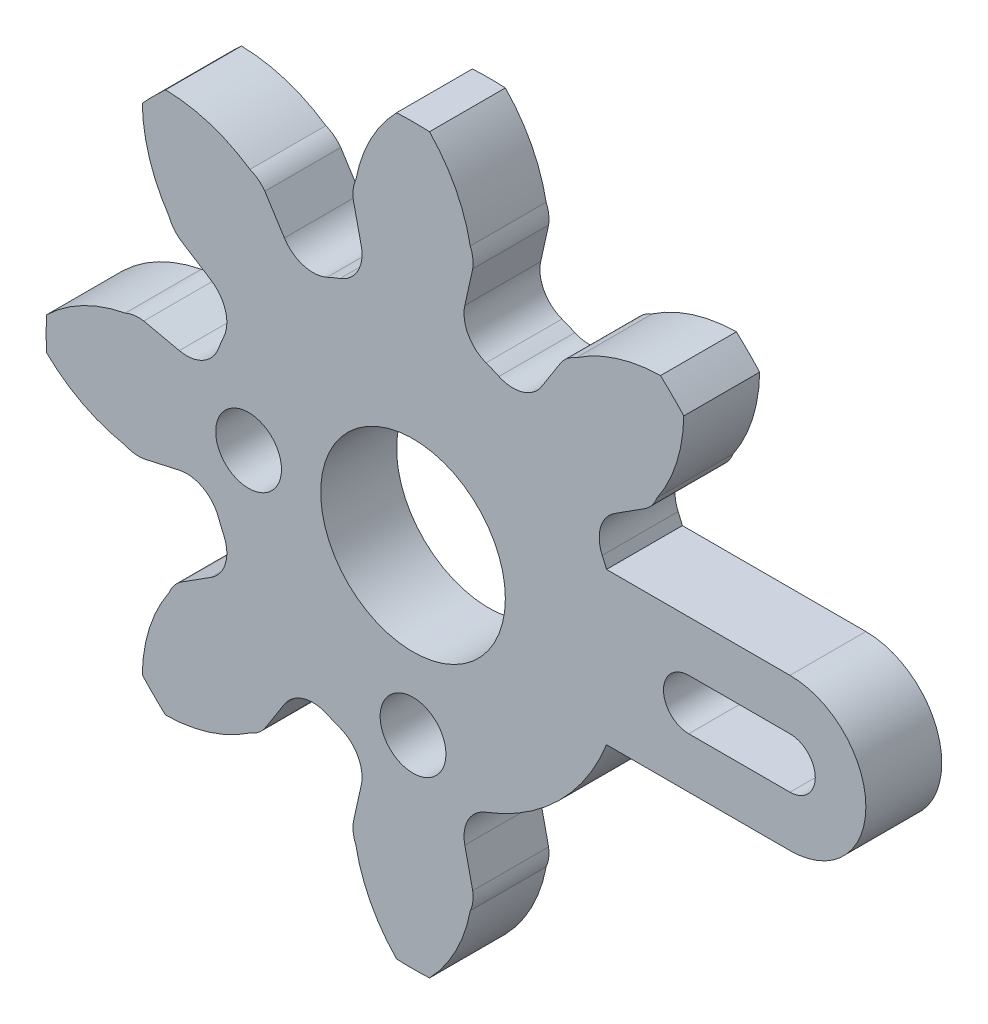
SolidWorks part; units mm, degrees
material "Acrílico (médio-alto impacto)"
ref_plane "Plano frontal" through (0, 0, 0) normal (0, 0, 1) x (1, 0, 0)
ref_plane "Plano superior" through (0, 0, 0) normal (0, 1, 0) x (1, 0, 0)
ref_plane "Plano direito" through (0, 0, 0) normal (1, 0, 0) x (0, 0, -1)
sketch "Posicionamentos" plane through (0, 0, 0) normal (0, 0, 1) x (1, 0, 0)
  circle A0 centre (0, 0) radius 14.5
  circle A1 centre (0, 0) radius 11.6
  circle A2 centre (0, 0) radius 8.2157
  circle A3 centre (0, 0) radius 10.9004
  dimension "De" = 29
  dimension "DP" = 23.2
  dimension "DI" = 16.4314
  dimension "DB" = 21.8009
sketch "Dente" plane through (0, 0, 0) normal (0, 0, 1) x (1, 0, 0)
  line L0 (0, 0) -> (0, 14.5) construction
  line L1 (0, 0) -> (0, 14.5) construction
  line L2 (2.3589, 10.6421) -> (1.7779, 8.021)
  line L3 (2.263, 11.3771) -> (0, 0) construction
  line L4 (-2.3589, 10.6421) -> (-1.7779, 8.021)
  circle A0 centre (0, 0) radius 14.5 construction
  arc A1 (0.6509, 14.4854) -> (2.263, 11.3771) centre (-3.7209, 10.2457) cw
  circle A2 centre (0, 0) radius 11.6 construction
  arc A3 (2.263, 11.3771) -> (2.3589, 10.6421) centre (1.0702, 10.8478) cw
  circle A4 centre (0, 0) radius 10.9004 construction
  circle A5 centre (0, 0) radius 8.2157 construction
  arc A6 (-2.263, 11.3771) -> (-2.3589, 10.6421) centre (-1.0702, 10.8478) ccw
  arc A7 (-0.6509, 14.4854) -> (-2.263, 11.3771) centre (3.7209, 10.2457) ccw
  arc A8 (-1.7779, 8.021) -> (1.7779, 8.021) centre (0, 0) cw
  arc A9 (-0.6509, 14.4854) -> (0.6509, 14.4854) centre (0, 0) cw
  arc A10 (-2.263, 11.3771) -> (2.263, 11.3771) centre (0, 0) cw construction
  dimension "R" = 6.09
  dimension "R1" = 1.305
  dimension "alpha" = 11.25
  dimension "Aposicionador" = 0
  dimension "D1" = 4.5553
sketch "Encaixe" plane through (0, 0, 0) normal (0, 0, 1) x (1, 0, 0)
  line L0 (10.9004, 0) -> (14.9004, 0) construction
  line L1 (10.9004, 1) -> (14.9004, 1)
  line L2 (10.9004, -1) -> (14.9004, -1)
  line L4 (0, 3) -> (14.9004, 3)
  line L5 (0, 3) -> (0, -3)
  line L6 (0, -3) -> (14.9004, -3)
  line L7 (14.9004, 3) -> (14.9004, -3) construction
  line L8 (7.4502, -3) -> (7.4502, 3) construction
  line L9 (0, 0) -> (14.9004, 0) construction
  arc A0 (10.9004, 1) -> (10.9004, -1) centre (10.9004, 0) ccw
  arc A1 (14.9004, -1) -> (14.9004, 1) centre (14.9004, 0) ccw
  arc A2 (14.9004, 3) -> (14.9004, -3) centre (14.9004, 0) cw
  circle A3 centre (0, 0) radius 10.9004 construction
  point P2 (12.9004, 0)
  point P8 (7.4502, 0)
  dimension "D1" = 4
  dimension "D2" = 6
  dimension "D3" = 2
sketch "Furos" plane through (0, 0, 0) normal (0, 0, 1) x (1, 0, 0)
  line L0 (0, -6.5) -> (0, 0) construction
  line L1 (0, 0) -> (-6.5, 0) construction
  circle A0 centre (0, 0) radius 6.5
  dimension "D1" = 13
extrude "Base" add sketch "Posicionamentos" along normal blind 3 contours A2
hole_wizard "Furo de diâmetro Ø2.6 (2.6)1" positions "Esboço8" profile "Esboço9" hole size "Ø2.6" standard "ISO" end condition through all
sketch "Esboço8" plane through (0, 0, 3) normal (0, 0, 1) x (1, 0, 0)
  point P0 (0, -6.5)
  point P3 (-6.5, 0)
sketch "Esboço9" plane through (0, -6.5, 3) normal (1, 0, 0) x (0, -1, 0)
  line L0 (0, 0) -> (0, 3)
  line L1 (0, 3) -> (1.3, 3)
  line L2 (1.3, 3) -> (1.3, 0)
  line L5 (1.3, 0) -> (0, 0)
  line L11 (0, -6.35) -> (0, 107.95) construction
  dimension "Thru Hole Dia." = 2.6
  dimension "Thru Hole Depth" = 3
extrude "Base Dente" add sketch "Dente" along normal through all
fillet "Raio Dente" radius 1.3424 2 edges at (-1.7779, 8.021, 1.5) (1.7779, 8.021, 1.5)
pattern_circular "PadrãoCircular1" count 8 over 360 about axis through (0, 0, 0) along (0, 0, 1) skipping 2, 3 of "Base Dente", "Raio Dente"
extrude "Ressalto-extrusão1" add sketch "Encaixe" along normal through all
hole_wizard "Furo de diâmetro Ø7.3 (7.3)1" positions "Esboço4" profile "Esboço5" hole size "Ø7.3" standard "ISO" end condition through all
sketch "Esboço4" plane through (0, 0, 3) normal (0, 0, 1) x (1, 0, 0)
  point P0 (0, 0)
sketch "Esboço5" plane through (0, 0, 3) normal (1, 0, 0) x (0, -1, 0)
  line L0 (0, 0) -> (0, 3)
  line L1 (0, 3) -> (3.65, 3)
  line L2 (3.65, 3) -> (3.65, 0)
  line L5 (3.65, 0) -> (0, 0)
  line L11 (0, -6.35) -> (0, 107.95) construction
  dimension "Thru Hole Dia." = 7.3
  dimension "Thru Hole Depth" = 3
equation "\"Z\"= 8"
equation "\"M\"= 2.9'Módulo"
equation "\"DP\"= \"Z\" * \"M\""
equation "\"P\"= \"M\" * pi'Passo"
equation "\"S\"= \"P\" / 2'Espessura Circular"
equation "\"V\"= \"S\"'Vão"
equation "\"sc\"= 1"
equation "\"de\"= \"M\" * ( \"Z\" + 2 )'Diâmetro Externo"
equation "\"di\"= \"M\" * ( \"Z\" - 2.334 )'Diâmetro Interno"
equation "\"Phi\"= 20'ângulo de pressão"
equation "\"db\"= \"DP\" * cos ( \"Phi\" )'Diâmetro do círculo de base"
equation "\"a\"= \"M\"'Altura da cabeça do dente"
equation "\"b\"= 1.167 * \"M\"'Altura do pé do dente"
equation "\"h\"= \"a\" + \"b\"'Altura do dente"
equation "\"e\"= .167 * \"M\"'Folga no pé do dente"
equation "\"alpha\"= 90 / \"Z\"'ângulo do dente"
equation "\"f\"= \"ValorF@Padrão\""
equation "\"f1\"= \"ValorF1@Padrão\""
equation "\"r\"= \"f\" * \"M\" 'Raio do dente"
equation "\"r1\"= \"f1\" * \"M\"'Rario 1 do dente"
equation "\"De@Posicionamentos\" = \"de\""
equation "\"DP@Posicionamentos\" = \"DP\""
equation "\"DI@Posicionamentos\" = \"di\""
equation "\"DB@Posicionamentos\" = \"db\""
equation "\"R@Dente\" = \"r\""
equation "\"R1@Dente\" = \"r1\""
equation "\"alpha@Dente\" = \"alpha\""
equation "\"D1@PadrãoCircular1\"=\"Z\""
equation "\"rd\"= ( \"db\" - \"di\" ) / 4"
equation "\"D1@Raio Dente\"=\"rd\""
equation "\"Posicionador\"= 1"
equation "\"Aposicionador\"= IIF ( \"Posicionador\" = 0 , 0 , ( \"alpha\" * 2 ) )"
equation "\"D1@Dente\"=\"S\""
